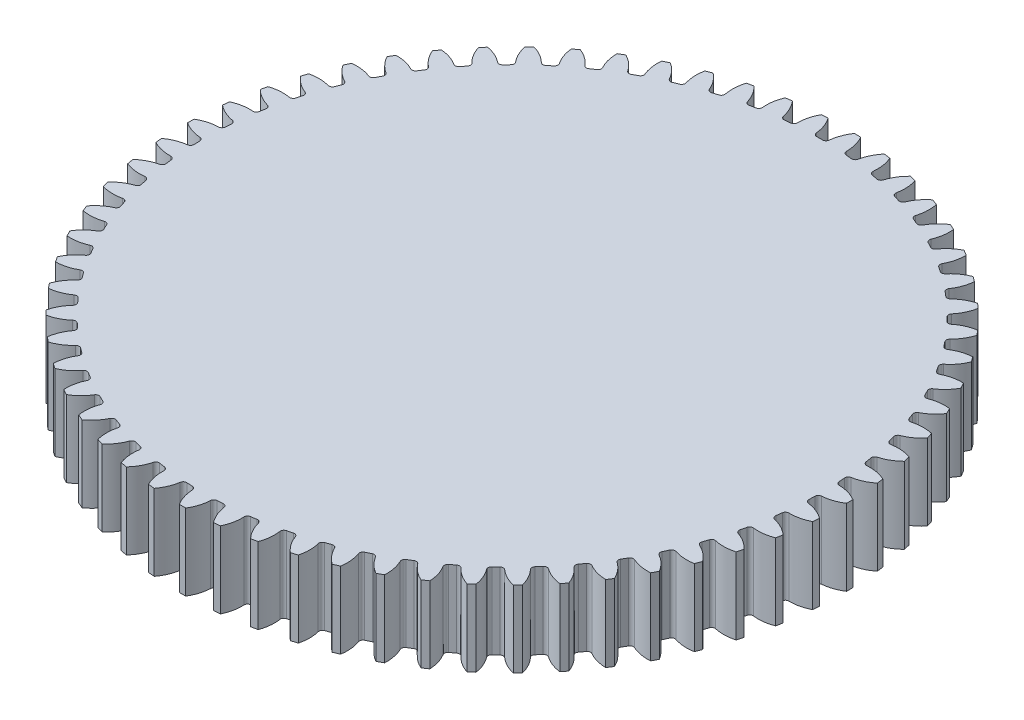
SolidWorks part; units mm, degrees
other "Base Gear" parameters "D1"=86.4588, "D2"=31.9281, "D3"=1.4393, "D4"=1.4984, "D5"=3.4328
ref_plane "Front Plane" through (0, 0, 0) normal (0, 0, 1) x (1, 0, 0)
ref_plane "Top Plane" through (0, 0, 0) normal (0, 1, 0) x (1, 0, 0)
ref_plane "Right Plane" through (0, 0, 0) normal (1, 0, 0) x (0, 0, -1)
sketch "Pole" plane through (0, 0, 0) normal (1, 0, 0) x (0, 0, -1)
  line L0 (0, 5) -> (0, -5) construction
  point P4 (0, 0)
sketch "Main Body" plane through (0, 0, 0) normal (0, 1, 0) x (1, 0, 0)
  circle A1 centre (0, 0) radius 21.6
  dimension "D2" = 43.2
extrude "Main Body Extrude" add sketch "Main Body" along normal mid plane 5 contours A1
sketch "Sketch5" plane through (0, 0, 0) normal (0, 1, 0) x (1, 0, 0)
  line L0 (0, 0) -> (0, 21.6) construction
  line L1 (-0.405, 20.1559) -> (0, 0) construction
  line L2 (0, 19.4507) -> (-0.5612, 20.9925) construction
  arc A0 (0.8663, 21.5826) -> (-0.8663, 21.5826) centre (0, 0) ccw
  arc A1 (0.5612, 20.9925) -> (-0.5612, 20.9925) centre (0, 0) ccw construction
  arc A2 (0.405, 20.1559) -> (-0.405, 20.1559) centre (0, 0) ccw
  arc A3 (-0.8663, 21.5826) -> (-0.405, 20.1559) centre (-3.003, 20.1037) cw
  arc A4 (0.8663, 21.5826) -> (0.405, 20.1559) centre (3.003, 20.1037) ccw
  dimension "D1" = 43.2
  dimension "D2" = 42
  dimension "D3" = 1.44
  dimension "D4" = 20
  dimension "D5" = 1.1225
extrude "Cut-Extrude1" cut sketch "Sketch5" against normal through all both and the other way through all
fillet "Fillet1" radius 0.228 2 edges at (0.405, 0, -20.1559) (-0.405, 0, -20.1559)
pattern_circular "CirPattern2" count 63 over 360 about axis through (0, 0, 0) along (0, 1, 0) of "Fillet1", "Cut-Extrude1"
equation "\"pitch diameter\"= 42"
equation "\"pressure angle\"= 20"
equation "\"module\"= 0.6mm"
equation "\"Outer Diameter\"= ( \"tooth\" + 2 ) * \"module\""
equation "\"backlash\"= 0.3 * \"module\""
equation "\"arc length\"= ( ( \"module\" * pi ) / 2 ) + \"backlash\""
equation "\"tooth\"= \"pitch diameter\" / \"module\""
equation "\"tooth depth\"= IIF ( \"module\" <= 1.25 , 2.4 * \"module\" , 2.25 * \"module\" )"
equation "\"fillet radius\"= 0.38 * \"module\""
equation "\"D2@Main Body\" = \"Outer Diameter\""
equation "\"D1@Sketch5\"=\"Outer Diameter\""
equation "\"D2@Sketch5\"=\"pitch diameter\""
equation "\"D3@Sketch5\"=\"tooth depth\""
equation "\"D4@Sketch5\"=\"pressure angle\""
equation "\"D5@Sketch5\"=\"arc length\""
equation "\"D1@Fillet1\"=\"fillet radius\""
equation "\"D1@CirPattern2\"= \"tooth Arbiturary\""
equation "\"tooth Arbiturary\"= 63"
